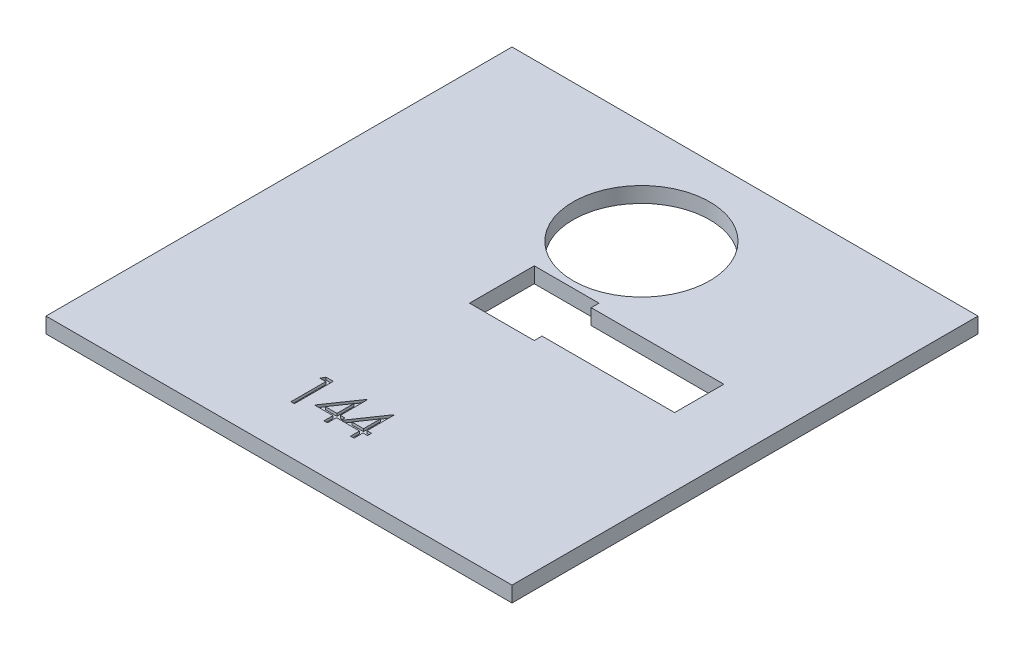
SolidWorks part; units mm, degrees
material "Acrylic (Medium-high impact)"
ref_plane "Front Plane" through (0, 0, 0) normal (0, 0, 1) x (1, 0, 0)
ref_plane "Top Plane" through (0, 0, 0) normal (0, 1, 0) x (1, 0, 0)
ref_plane "Right Plane" through (0, 0, 0) normal (1, 0, 0) x (0, 0, -1)
sketch "Sketch1" plane through (0, 0, 0) normal (0, 1, 0) x (1, 0, 0)
  line L1 (-90, 90) -> (90, 90)
  line L2 (-90, 90) -> (-90, -90)
  line L3 (-90, -90) -> (90, -90)
  line L4 (90, 90) -> (90, -90)
  line L5 (-90, 90) -> (90, -90) construction
  line L6 (-90, -90) -> (90, 90) construction
  circle A0 centre (0, 50) radius 26.4
  point P0 (0, 0)
  dimension "D3" = 52.8
  dimension "D1" = 180
  dimension "D2" = 180
  dimension "D4" = 40
extrude "Boss-Extrude2" add sketch "Sketch1" along normal blind 6
sketch "Sketch2" plane through (0, 6, 0) normal (0, 1, 0) x (1, 0, 0)
  line L0 (-90, 90) -> (-90, -90) construction
  line L1 (-12.5, 21.1) -> (12.5, 21.1)
  line L2 (-12.5, 21.1) -> (-12.5, -3.9)
  line L3 (-12.5, -3.9) -> (12.5, -3.9)
  line L4 (12.5, 21.1) -> (12.5, 18.1)
  line L5 (12.5, -0.9) -> (12.5, -3.9)
  line L6 (12.5, 18.1) -> (63.71, 18.1)
  line L8 (12.5, -0.9) -> (63.71, -0.9)
  line L9 (63.71, 18.1) -> (63.71, -0.9)
  circle A0 centre (0, 50) radius 26.4 construction
  dimension "D5" = 3
  dimension "D1" = 25
  dimension "D2" = 25
  dimension "D3" = 77.5
  dimension "D4" = 28.9
  dimension "D6" = 3
  dimension "D7" = 51.21
extrude "Cut-Extrude1" cut sketch "Sketch2" against normal blind 10
sketch "Sketch3" plane through (0, 6, 0) normal (0, 1, 0) x (1, 0, 0)
  text T0 "144" font "Century Gothic" height 15
extrude "Cut-Extrude2" cut sketch "Sketch3" against normal blind 1
